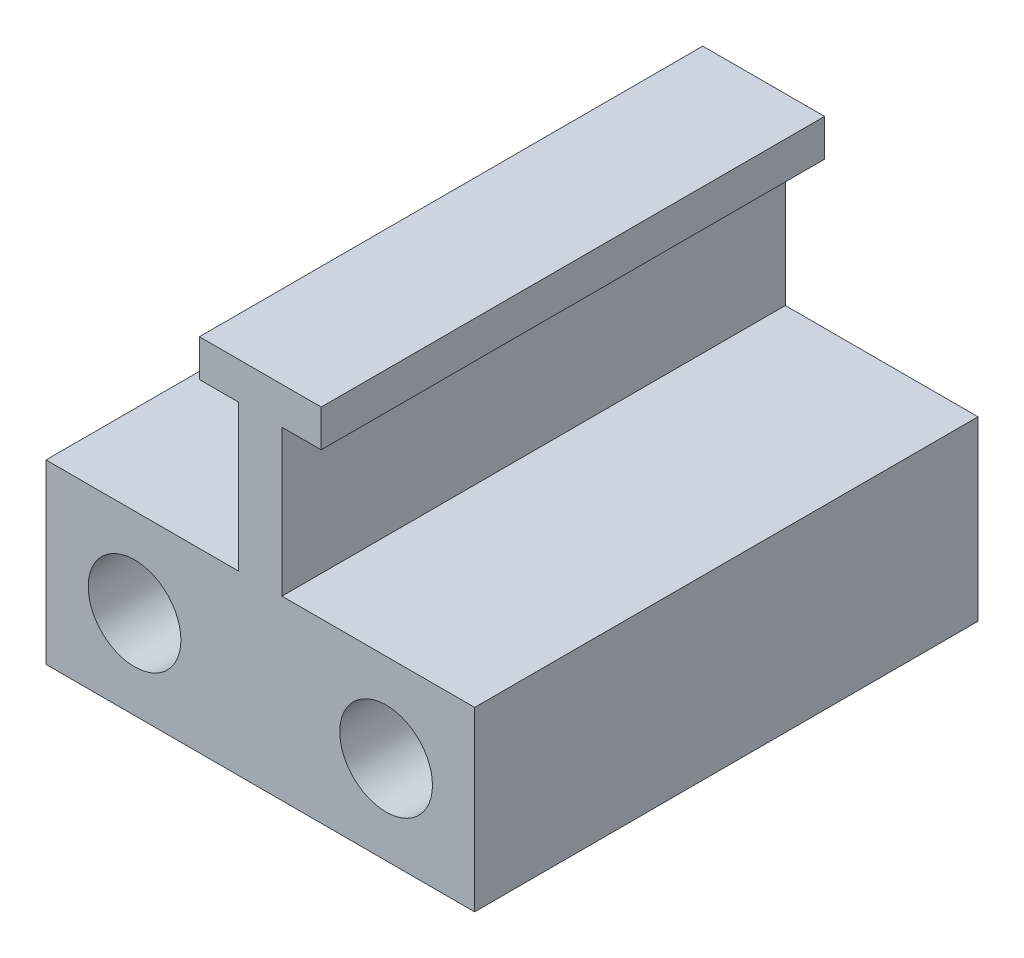
SolidWorks part; units mm, degrees
ref_plane "Front Plane" through (0, 0, 0) normal (0, 0, 1) x (1, 0, 0)
ref_plane "Top Plane" through (0, 0, 0) normal (0, 1, 0) x (1, 0, 0)
ref_plane "Right Plane" through (0, 0, 0) normal (1, 0, 0) x (0, 0, -1)
sketch "Sketch1" plane through (0, 0, 0) normal (0, 0, 1) x (1, 0, 0)
  line L0 (0, 39.2233) -> (0, -19.1029) construction
  line L1 (-9.85, 39.2233) -> (9.85, 39.2233)
  line L2 (-34.6762, 9.5495) -> (-34.6762, -19.1029)
  line L3 (-34.6762, -19.1029) -> (34.6762, -19.1029)
  line L4 (34.6762, 9.5495) -> (34.6762, -19.1029)
  line L7 (-34.6762, 9.5495) -> (-10.165, 9.5495)
  line L8 (-9.85, 39.2233) -> (-9.85, 33.2233)
  line L11 (34.6762, 9.5495) -> (10.165, 9.5495)
  line L12 (9.85, 39.2233) -> (9.85, 33.2233)
  line L14 (-9.85, 33.2233) -> (-3.5, 33.2233)
  line L16 (-10.165, 9.5495) -> (-3.5, 9.5495)
  line L17 (-3.5, 33.2233) -> (-3.5, 9.5495)
  line L18 (9.85, 33.2233) -> (3.5, 33.2233)
  line L20 (10.165, 9.5495) -> (3.5, 9.5495)
  line L21 (3.5, 33.2233) -> (3.5, 9.5495)
  circle A0 centre (-20.35, -4.7767) radius 7.5
  circle A1 centre (20.35, -4.7767) radius 7.5
  dimension "D2" = 15
  dimension "D3" = 15
  dimension "D1" = 40.7
  dimension "D4" = 14.3262
  dimension "D5" = 14.3262
  dimension "D6" = 14.3262
  dimension "D7" = 14.3262
  dimension "D8" = 44
  dimension "D9" = 19.7
  dimension "D11" = 6.35
  dimension "D12" = 6.35
  dimension "D13" = 6
  dimension "D14" = 6
  dimension "D15" = 14.3262
  dimension "D16" = 14.3262
extrude "Boss-Extrude1" add sketch "Sketch1" along normal blind 81.44
